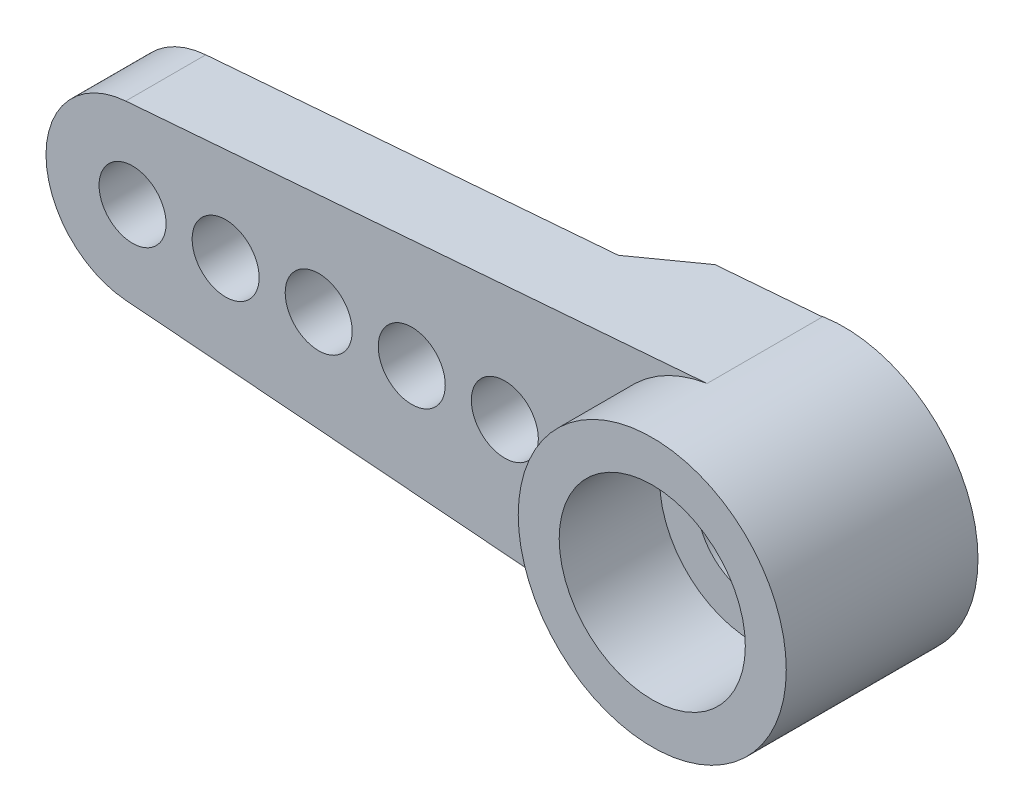
SolidWorks part; units mm, degrees
ref_plane "Plano frontal" through (0, 0, 0) normal (0, 0, 1) x (1, 0, 0)
ref_plane "Plano superior" through (0, 0, 0) normal (0, 1, 0) x (1, 0, 0)
ref_plane "Plano direito" through (0, 0, 0) normal (1, 0, 0) x (0, 0, -1)
sketch "Esboço1" plane through (0, 0, 0) normal (0, 0, 1) x (1, 0, 0)
  circle A0 centre (0, 0) radius 2.45
  circle A1 centre (0, 0) radius 3.6
  dimension "D1" = 7.2
  dimension "D2" = 4.9
extrude "Ressalto-extrusão1" add sketch "Esboço1" along normal blind 2.8 and the other way blind 0.15
sketch "Esboço2" plane through (0, 0, -0.15) normal (0, 0, -1) x (-1, 0, 0)
  circle A0 centre (0, 0) radius 2.5
  circle A1 centre (0, 0) radius 1
  dimension "D1" = 2
extrude "Ressalto-extrusão2" add sketch "Esboço2" along normal blind 0.5 separate body
sketch "Esboço3" plane through (0, 0, -0.15) normal (0, 0, -1) x (-1, 0, 0)
  circle A0 centre (0, 0) radius 3.6
  circle A1 centre (0, 0) radius 2.45
  dimension "D1" = 7.2
  dimension "D2" = 4.9
extrude "Ressalto-extrusão3" add sketch "Esboço3" along normal blind 2.2
sketch "Esboço4" plane through (0, 0, 0) normal (0, 1, 0) x (1, 0, 0)
  line L0 (3.6, 2.35) -> (-3.6, 2.35) construction
  line L1 (-18.325, 1.39) -> (3.675, 1.39)
  line L2 (-18.325, 1.39) -> (-18.325, -0.76)
  line L3 (3.675, 1.39) -> (3.675, -5.4692) construction
  line L5 (3.675, -0.76) -> (-18.325, -0.76)
  line L6 (3.675, 1.39) -> (3.675, -0.76)
  point P0 (0, 0)
  dimension "D1" = 0.96
  dimension "D2" = 22
extrude "Ressalto-extrusão4" add sketch "Esboço4" along normal mid plane 7.2
sketch "Esboço5" plane through (0, 0, 0.76) normal (0, 0, 1) x (1, 0, 0)
  line L0 (0, 0) -> (-16, 0) construction
  line L1 (-16, 0) -> (-16, -7.6538) construction
  line L3 (-16.75, 0) -> (-18.05, 0) construction
  line L4 (-0.5669, -3.5551) -> (-16.1836, -2.3177)
  line L5 (-0.5669, 3.5551) -> (-16.1836, 2.3177)
  line L6 (5.6455, 5.6158) -> (5.6455, -6.5456)
  line L15 (-22.4536, -6.5456) -> (5.6455, -6.5456)
  line L16 (-22.4536, 5.6158) -> (-22.4536, -6.5456)
  line L17 (5.6455, 5.6158) -> (-22.4536, 5.6158)
  circle A0 centre (-16, 0) radius 0.75
  arc A1 (-16.1836, 2.3177) -> (-16.1836, -2.3177) centre (-16, 0) ccw
  arc A2 (-0.5669, -3.5551) -> (-0.5669, 3.5551) centre (0, 0) ccw
  dimension "D2" = 1.5
  dimension "D4" = 4.65
  dimension "D1" = 16
  dimension "D3" = 1.3
extrude "Corte-extrusão2" cut sketch "Esboço5" against normal blind 7.2
sketch "Esboço7" plane through (0, 0, 2.8) normal (0, 0, 1) x (1, 0, 0)
  circle A0 centre (0, 0) radius 2.5
extrude "Corte-extrusão3" cut sketch "Esboço7" against normal blind 2.7
sketch "Esboço8" plane through (0, 0, 0.1) normal (0, 0, 1) x (1, 0, 0)
  line L0 (0, 0) -> (-16, 0) construction
  line L1 (-6, 0) -> (-6, -4.249) construction
  line L3 (-8.5, -4.249) -> (-8.5, 0) construction
  line L5 (-11, 0) -> (-11, -4.249) construction
  line L9 (-13.5, 0) -> (-13.5, -4.249) construction
  line L15 (-16, -4.249) -> (-16, 0) construction
  circle A0 centre (0, 0) radius 1.5
  circle A1 centre (-6, 0) radius 0.9
  circle A2 centre (-8.5, 0) radius 0.9
  circle A3 centre (-11, 0) radius 0.9
  circle A4 centre (-13.5, 0) radius 0.9
  circle A5 centre (-16, 0) radius 0.9
  dimension "D1" = 3
  dimension "D7" = 1.8
  dimension "D8" = 1.8
  dimension "D9" = 1.8
  dimension "D10" = 1.8
  dimension "D11" = 1.8
  dimension "D2" = 6
  dimension "D3" = 8.5
  dimension "D4" = 11
  dimension "D5" = 13.5
  dimension "D6" = 16
extrude "Corte-extrusão4" cut sketch "Esboço8" against normal mid plane 13.8
sketch "Esboço10" plane through (0, 0, -1.39) normal (0, 0, -1) x (-1, 0, 0)
  line L0 (5.1, -3.1959) -> (5.1, -2.3959) construction
  line L1 (18.325, 0) -> (3.6, 0) construction
  line L3 (5.1, 3.1959) -> (5.1, 2.3959) construction
  line L4 (5.1, -3.1959) -> (5.1, -2.3959)
  line L5 (5.1, -2.3959) -> (2.6869, -2.3959)
  line L6 (5.1938, -0.4) -> (3.5777, -0.4)
  line L7 (5.1938, 0.4) -> (3.5777, 0.4)
  line L8 (5.1, -3.1959) -> (0, -3.6)
  line L9 (5.1, 3.1959) -> (0, 3.6)
  line L10 (5.1, 2.3959) -> (2.6869, 2.3959)
  line L11 (5.1, 3.1959) -> (5.1, 2.3959)
  line L13 (5.1, 2.3959) -> (5.1, 3.1959) construction
  arc A0 (16.1836, -2.3177) -> (16.1836, 2.3177) centre (16, 0) ccw construction
  arc A1 (3.5777, -0.4) -> (3.5777, 0.4) centre (0, 0) ccw
  arc A2 (0, -3.6) -> (2.6869, -2.3959) centre (0, 0) ccw
  arc A3 (2.6869, 2.3959) -> (0, 3.6) centre (0, 0) ccw
  arc A4 (5.1938, 0.4) -> (5.1938, -0.4) centre (6, 0) ccw
  circle M6 centre (6, 0) radius 0.9
  line M10 (16.1836, 2.3177) -> (0.5669, 3.5551)
  arc M11 (0.5669, 3.5551) -> (0.5669, -3.5551) centre (0, 0) cw
  line M12 (0.5669, -3.5551) -> (16.1836, -2.3177)
  dimension "D1" = 0.8
  dimension "D2" = 0.4
  dimension "D3" = 0.4
extrude "Ressalto-extrusão5" add sketch "Esboço10" along normal blind 0.95 contours L4 L5 M11 M12 | L7 L6 M6 M11 | L11 L10 M10 M11
sketch "Esboço11" plane through (0, 0, 0) normal (0, 1, 0) x (1, 0, 0)
  line L0 (-5.1, 1.39) -> (-2.0456, 3.1535)
  line L2 (-5.1, 1.39) -> (-5.859, 1.39)
  line L3 (-5.1, 1.39) -> (-16.1836, 1.39) construction
  line L4 (-5.859, 1.39) -> (-5.859, 3.1535)
  line L5 (-5.859, 3.1535) -> (-2.0456, 3.1535)
extrude "Corte-extrusão5" cut sketch "Esboço11" against normal blind 4.95 and the other way blind 12
sketch "Esboço12" plane through (0, 0, 0.76) normal (0, 0, 1) x (1, 0, 0)
  line L0 (0, 0) -> (-18.325, 0) construction
  line L1 (0, 0) -> (0, -3.6) construction
  arc A0 (-16.1836, 2.3177) -> (-16.1836, -2.3177) centre (-16, 0) ccw construction
  circle A1 centre (0, 0) radius 3.6 construction
